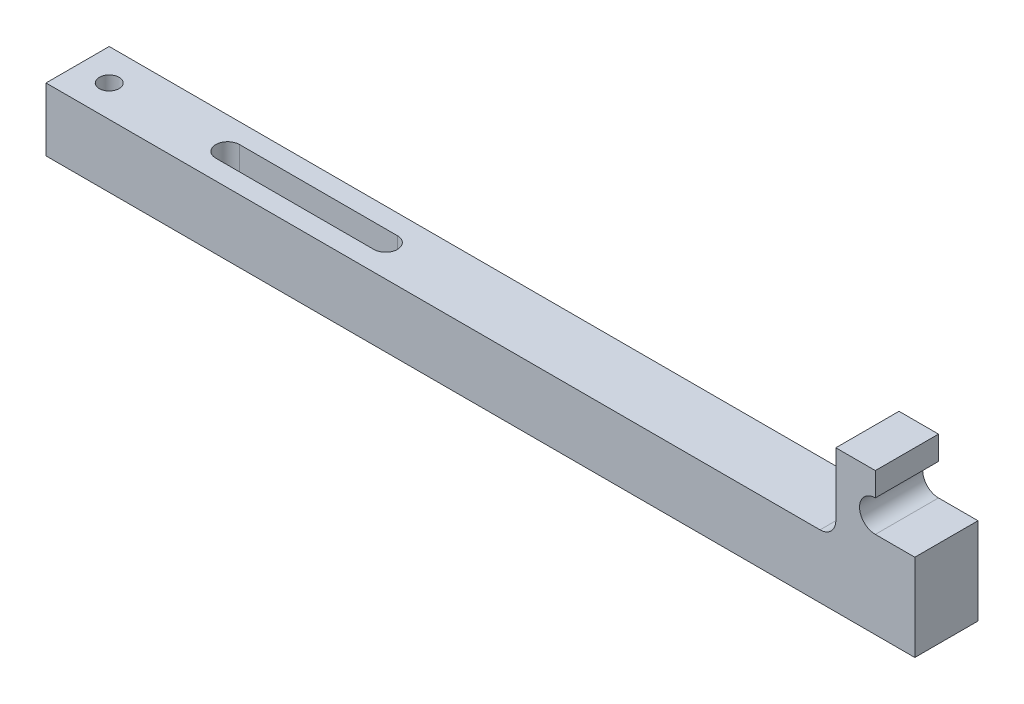
SolidWorks part; units mm, degrees
ref_plane "Front Plane" through (0, 0, 0) normal (0, 0, 1) x (1, 0, 0)
ref_plane "Top Plane" through (0, 0, 0) normal (0, 1, 0) x (1, 0, 0)
ref_plane "Right Plane" through (0, 0, 0) normal (1, 0, 0) x (0, 0, -1)
sketch "Sketch1" plane through (0, 0, 0) normal (0, 0, 1) x (1, 0, 0)
  line L1 (-29.5318, 7.0518) -> (-24.5318, 7.0518)
  line L2 (-24.5318, 7.0518) -> (-24.5318, -3.9482)
  line L3 (-24.5318, -3.9482) -> (-134.5318, -3.9482)
  line L4 (-29.5318, 11.0518) -> (-29.5318, 14.0518)
  line L5 (-29.5318, 14.0518) -> (-34.5318, 14.0518)
  line L6 (-34.5318, 14.0518) -> (-34.5318, 6.0518)
  line L7 (-134.5318, -3.9482) -> (-134.5318, 4.0518)
  line L8 (-134.5318, 4.0518) -> (-36.5318, 4.0518)
  arc A0 (-29.5318, 11.0518) -> (-29.5318, 7.0518) centre (-29.5318, 9.0518) ccw
  arc A1 (-36.5318, 4.0518) -> (-34.5318, 6.0518) centre (-36.5318, 6.0518) ccw
extrude "Boss-Extrude2" add sketch "Sketch1" along normal blind 8
sketch "Sketch3" plane through (0, 4.0518, 0) normal (0, 1, 0) x (1, 0, 0)
  circle A0 centre (-130.5318, -4) radius 1.25
extrude "Cut-Extrude1" cut sketch "Sketch3" against normal blind 8
sketch "Sketch4" plane through (0, 4.0518, 0) normal (0, 1, 0) x (1, 0, 0)
  line L0 (-115.5318, -2.5) -> (-95.5318, -2.5)
  line L1 (-115.5318, -5.5) -> (-95.5318, -5.5)
  arc A0 (-115.5318, -2.5) -> (-115.5318, -5.5) centre (-115.5318, -4) ccw
  arc A1 (-95.5318, -5.5) -> (-95.5318, -2.5) centre (-95.5318, -4) ccw
extrude "Cut-Extrude2" cut sketch "Sketch4" against normal blind 8
